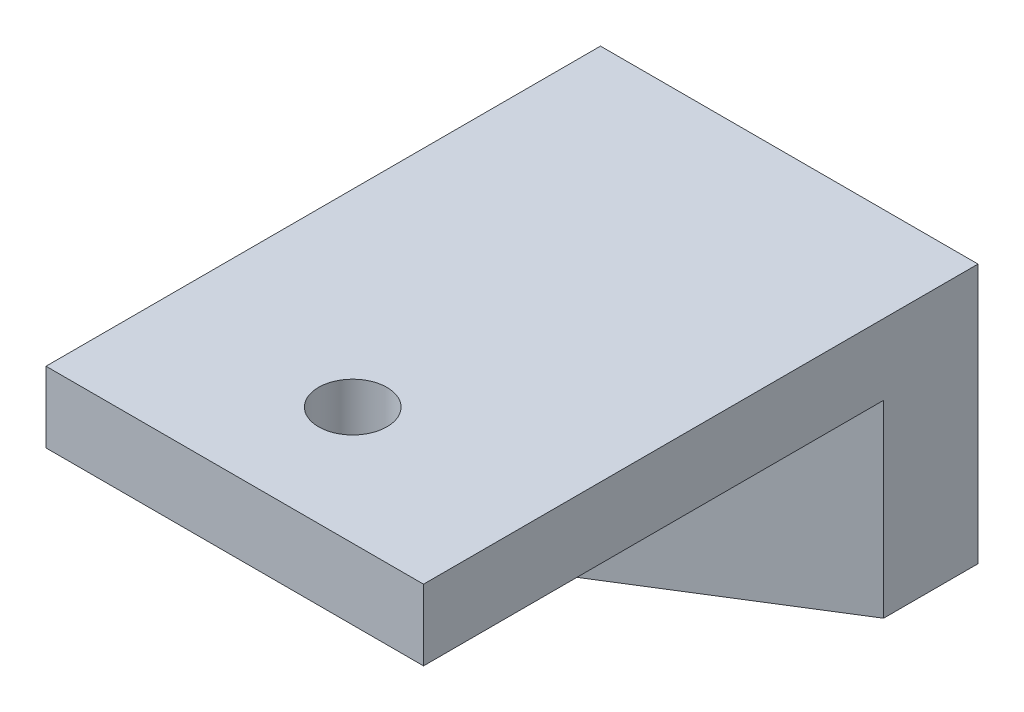
SolidWorks part; units mm, degrees
ref_plane "Front Plane" through (0, 0, 0) normal (0, 0, 1) x (1, 0, 0)
ref_plane "Top Plane" through (0, 0, 0) normal (0, 1, 0) x (1, 0, 0)
ref_plane "Right Plane" through (0, 0, 0) normal (1, 0, 0) x (0, 0, -1)
sketch "Sketch1" plane through (0, 0, 0) normal (0, 1, 0) x (1, 0, 0)
  line L0 (-47.1345, 16.0695) -> (-47.1345, 12.0695)
  line L1 (-47.1345, 16.0695) -> (-31.1345, 16.0695) construction
  line L2 (-31.1345, 16.0695) -> (-31.1345, 12.0695)
  line L3 (-39.1345, 16.0695) -> (-39.1345, 1.6211) construction
  line L4 (-39.1345, 16.0695) -> (-39.1345, 11.0695) construction
  line L5 (-47.1345, 16.0695) -> (-39.1345, 11.0695)
  line L6 (-39.1345, 11.0695) -> (-31.1345, 16.0695)
  line L7 (-31.1345, 12.0695) -> (-39.1345, 7.0695)
  line L8 (-39.1345, 7.0695) -> (-47.1345, 12.0695)
extrude "Boss-Extrude1" add sketch "Sketch1" along normal blind 8
sketch "Sketch2" plane through (0, 8, 0) normal (0, 1, 0) x (1, 0, 0)
  line L0 (-47.1345, 16.0695) -> (-31.1345, 16.0695)
  line L1 (-31.1345, 16.0695) -> (-31.1345, -7.4305)
  line L2 (-31.1345, -7.4305) -> (-47.1345, -7.4305)
  line L3 (-47.1345, -7.4305) -> (-47.1345, 16.0695)
  dimension "D1" = 23.5
extrude "Boss-Extrude2" add sketch "Sketch2" along normal blind 3
sketch "Sketch3" plane through (0, 11, 0) normal (0, 1, 0) x (1, 0, 0)
  line L0 (-39.1345, -7.4305) -> (-39.1345, -2.4305) construction
  line L1 (-47.1345, -7.4305) -> (-31.1345, -7.4305) construction
  circle A0 centre (-39.1345, -2.4305) radius 1.45
extrude "Cut-Extrude1" cut sketch "Sketch3" against normal blind 3
